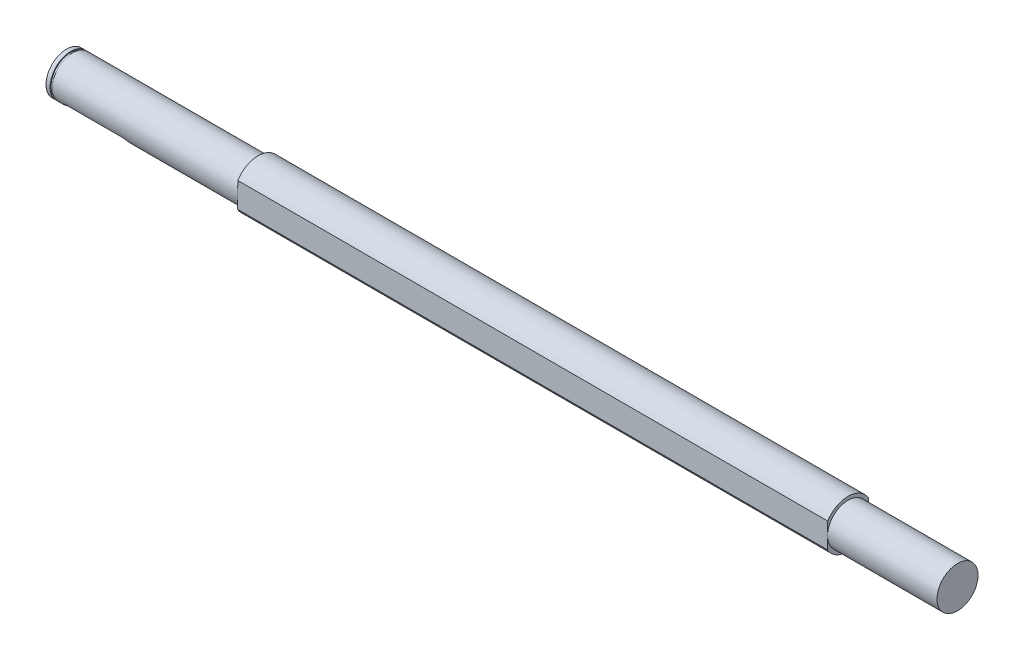
SolidWorks part; units mm, degrees
ref_plane "Ön Düzlem" through (0, 0, 0) normal (0, 0, 1) x (1, 0, 0)
ref_plane "Üst Düzlem" through (0, 0, 0) normal (0, 1, 0) x (1, 0, 0)
ref_plane "Sağ Düzlem" through (0, 0, 0) normal (1, 0, 0) x (0, 0, -1)
sketch "Çizim1" plane through (0, 0, 0) normal (0, 0, 1) x (1, 0, 0)
  line L0 (-325.5, 0) -> (325.5, 0)
  line L1 (-325.5, 0) -> (-325.5, 15)
  line L2 (-325.5, 15) -> (-185.5, 15)
  line L3 (-185.5, 15) -> (-185.5, 17.5)
  line L4 (-185.5, 17.5) -> (245.5, 17.5)
  line L5 (245.5, 17.5) -> (245.5, 15)
  line L6 (245.5, 15) -> (325.5, 15)
  line L7 (325.5, 15) -> (325.5, 0)
  point P2 (0, 0)
  dimension "D1" = 80
  dimension "D2" = 431
  dimension "D3" = 140
  dimension "D4" = 15
  dimension "D5" = 17.5
revolve "Döndür1" add sketch "Çizim1" angle 360 about L0
sketch "Çizim2" plane through (-185.5, 0, 0) normal (-1, 0, 0) x (0, 0, 1)
  line L0 (-14.8439, 9.2687) -> (-15.1517, -8.7564)
  line L1 (0, 0) -> (0, 5.6133) construction
  line L2 (14.8439, 9.2687) -> (15.1517, -8.7564)
  circle A0 centre (0, 0) radius 15 construction
  circle A1 centre (0, 0) radius 17.5 construction
  arc A2 (-14.8439, 9.2687) -> (-15.1517, -8.7564) centre (0, 0) ccw
  arc A3 (14.8439, 9.2687) -> (15.1517, -8.7564) centre (0, 0) cw
extrude "Kes-Ekstrüzyon1" cut sketch "Çizim2" against normal up to surface (431 mm away) up to face at (245.5, 0, 17.5)
sketch "Çizim3" plane through (0, 0, 0) normal (0, 1, 0) x (1, 0, 0)
  line L8 (-322.5, 15) -> (-322.5, 14.3)
  line L9 (-320.9, 14.3) -> (-322.5, 14.3)
  line L10 (-320.9, 15) -> (-320.9, 14.3)
  line L11 (-320.9, 15) -> (-322.5, 15)
  line L12 (-325.5, 0) -> (-290.1398, 0) construction
  line L13 (-325.5, 15) -> (-325.5, -15) construction
  dimension "D4" = 28.6
  dimension "D5" = 3
  dimension "D6" = 1.6
revolve "Kes-Döndür2" cut sketch "Çizim3" angle 360 about L12
sketch "Çizim5" plane through (-325.5, 0, 0) normal (-1, 0, 0) x (0, 0, 1)
  line L0 (0, 0) -> (23.3359, 0) construction
  line L1 (23.3359, 0) -> (-1.5775, -20.9048) construction
  circle A0 centre (0, 0) radius 15 construction
  dimension "D1" = 40
ref_plane "Düzlem1" through (0, -11.4907, 9.6418) normal (0, 0.766, -0.6428) x (0, -0.6428, -0.766)
sketch "Çizim6" plane through (0, -11.4907, 9.6418) normal (0, 0.766, -0.6428) x (0, -0.6428, -0.766)
  line L0 (0, 312.5) -> (0, 272.5) construction
  line L1 (5, 312.5) -> (5, 272.5)
  line L2 (-5, 312.5) -> (-5, 272.5)
  line L3 (-17.8763, 325.5) -> (14.6458, 325.5) construction
  arc A0 (5, 312.5) -> (-5, 312.5) centre (0, 312.5) ccw
  arc A1 (-5, 272.5) -> (5, 272.5) centre (0, 272.5) ccw
  point P3 (0, 292.5)
  dimension "D3" = 8
  dimension "D1" = 10
  dimension "D2" = 40
extrude "Kes-Ekstrüzyon2" cut sketch "Çizim6" along normal blind 5
